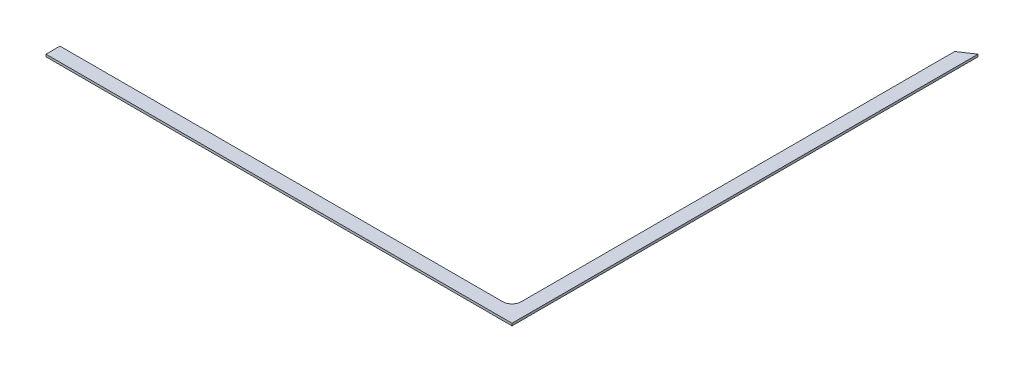
SolidWorks part; units mm, degrees
material "Epoxy, Unfilled"
ref_plane "Front Plane" through (0, 0, 0) normal (0, 0, 1) x (1, 0, 0)
ref_plane "Top Plane" through (0, 0, 0) normal (0, 1, 0) x (1, 0, 0)
ref_plane "Right Plane" through (0, 0, 0) normal (1, 0, 0) x (0, 0, -1)
sketch "Sketch2" plane through (0, 0, 0) normal (0, 1, 0) x (1, 0, 0)
  line L0 (0, 0) -> (0, 47.5)
  line L1 (0, 47.5) -> (1.5, 48.5)
  line L2 (1.5, 48.5) -> (1.5, -1.5)
  line L3 (1.5, -1.5) -> (-48.5, -1.5)
  line L4 (-48.5, -1.5) -> (-48.5, 0)
  line L5 (-48.5, 0) -> (0, 0)
  line L6 (0, 47.5) -> (1.5, 47.5) construction
  point P4 (0, 47.0099)
  dimension "D1" = 1.5
  dimension "D2" = 50
  dimension "D3" = 1
extrude "Boss-Extrude2" add sketch "Sketch2" along normal mid plane 0.25
fillet "Fillet2" radius 1 1 edges at (0, 0, 0)
